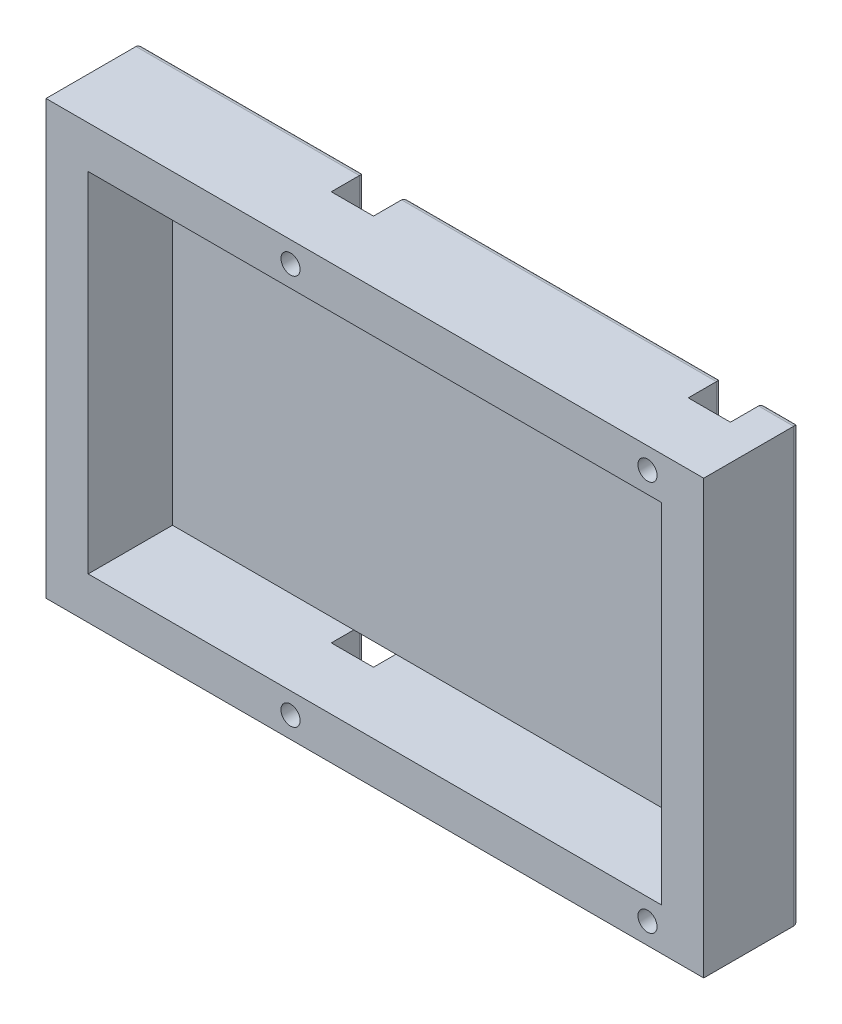
SolidWorks part; units mm, degrees
material "ABS"
ref_plane "Front" through (0, 0, 0) normal (0, 0, 1) x (1, 0, 0)
ref_plane "Top" through (0, 0, 0) normal (0, 1, 0) x (1, 0, 0)
ref_plane "Right" through (0, 0, 0) normal (1, 0, 0) x (0, 0, -1)
sketch "ｽｹｯﾁ1" plane through (0, 0, 0) normal (0, 0, 1) x (1, 0, 0)
  line L1 (58.5, 38.5) -> (-58.5, 38.5)
  line L2 (58.5, 38.5) -> (58.5, -38.5)
  line L3 (58.5, -38.5) -> (-58.5, -38.5)
  line L4 (-58.5, 38.5) -> (-58.5, -38.5)
  line L5 (58.5, 38.5) -> (-58.5, -38.5) construction
  line L6 (58.5, -38.5) -> (-58.5, 38.5) construction
  point P0 (0, 0)
  dimension "D1" = 117
  dimension "D2" = 77
extrude "ﾎﾞｽ - 押し出し1" add sketch "ｽｹｯﾁ1" along normal blind 17
sketch "ｽｹｯﾁ2" plane through (0, 0, 17) normal (0, 0, 1) x (1, 0, 0)
  line L1 (51, 31) -> (-51, 31)
  line L2 (51, 31) -> (51, -31)
  line L3 (51, -31) -> (-51, -31)
  line L4 (-51, 31) -> (-51, -31)
  line L5 (51, 31) -> (-51, -31) construction
  line L6 (51, -31) -> (-51, 31) construction
  point P0 (0, 0)
  dimension "D1" = 102
  dimension "D2" = 62
extrude "ｶｯﾄ - 押し出し1" cut sketch "ｽｹｯﾁ2" against normal offset from surface (15 mm away) 2 up to face at (0, 0, 0)
sketch "ｽｹｯﾁ4" plane through (0, 0, 0) normal (0, 0, -1) x (-1, 0, 0)
  line L0 (-58.5, -38.5) -> (-58.5, 38.5) construction
  line L1 (-58.5, 38.5) -> (58.5, 38.5) construction
  line L2 (58.5, -38.5) -> (-58.5, -38.5) construction
  circle A0 centre (15, 34.75) radius 1.7
  circle A1 centre (15, -34.75) radius 1.7
  circle A2 centre (-48.5, -34.75) radius 1.7
  circle A3 centre (-48.5, 34.75) radius 1.7
  dimension "D1" = 3.4
  dimension "D2" = 10
  dimension "D3" = 3.75
  dimension "D4" = 3.75
  dimension "D5" = 73.5
extrude "ｶｯﾄ - 押し出し2" cut sketch "ｽｹｯﾁ4" against normal through all
sketch "ｽｹｯﾁ5" plane through (0, 0, 0) normal (0, 0, -1) x (-1, 0, 0)
  line L0 (58.5, -38.5) -> (-58.5, -38.5) construction
  line L1 (-52.25, -31) -> (-44.75, -31)
  line L2 (-52.25, -31) -> (-52.25, -38.5)
  line L3 (-52.25, -38.5) -> (-44.75, -38.5)
  line L4 (-44.75, -31) -> (-44.75, -38.5)
  line L5 (-52.25, -31) -> (-44.75, -38.5) construction
  line L6 (-52.25, -38.5) -> (-44.75, -31) construction
  line L7 (-58.5, 38.5) -> (58.5, 38.5) construction
  line L8 (-52.25, 38.5) -> (-44.75, 38.5)
  line L9 (-52.25, 38.5) -> (-52.25, 31)
  line L10 (-52.25, 31) -> (-44.75, 31)
  line L11 (-44.75, 38.5) -> (-44.75, 31)
  line L12 (-52.25, 38.5) -> (-44.75, 31) construction
  line L13 (-52.25, 31) -> (-44.75, 38.5) construction
  line L14 (11.25, 38.5) -> (18.75, 38.5)
  line L15 (11.25, 38.5) -> (11.25, 31)
  line L16 (11.25, 31) -> (18.75, 31)
  line L17 (18.75, 38.5) -> (18.75, 31)
  line L18 (11.25, 38.5) -> (18.75, 31) construction
  line L19 (11.25, 31) -> (18.75, 38.5) construction
  line L20 (11.25, -31) -> (18.75, -31)
  line L21 (11.25, -31) -> (11.25, -38.5)
  line L22 (11.25, -38.5) -> (18.75, -38.5)
  line L23 (18.75, -31) -> (18.75, -38.5)
  line L24 (11.25, -31) -> (18.75, -38.5) construction
  line L25 (11.25, -38.5) -> (18.75, -31) construction
  point P0 (-48.5, -34.75)
  point P8 (-48.5, 34.75)
  point P14 (15, 34.75)
  point P20 (15, -34.75)
extrude "ｶｯﾄ - 押し出し3" cut sketch "ｽｹｯﾁ5" against normal blind 6
fillet "ﾌｨﾚｯﾄ2" radius 1 20 edges at (44.75, 34.75, 0) (48.5, 31, 0) (55.375, 38.5, 0) (52.25, 34.75, 0) (16.75, 38.5, 0) (-11.25, 34.75, 0) (-15, 31, 0) (-18.75, 34.75, 0) (-38.625, 38.5, 0) (-58.5, 0, 0) (-38.625, -38.5, 0) (-18.75, -34.75, 0) (-15, -31, 0) (-11.25, -34.75, 0) (52.25, -34.75, 0) (48.5, -31, 0) (44.75, -34.75, 0) (16.75, -38.5, 0) (55.375, -38.5, 0) (58.5, 0, 0)
